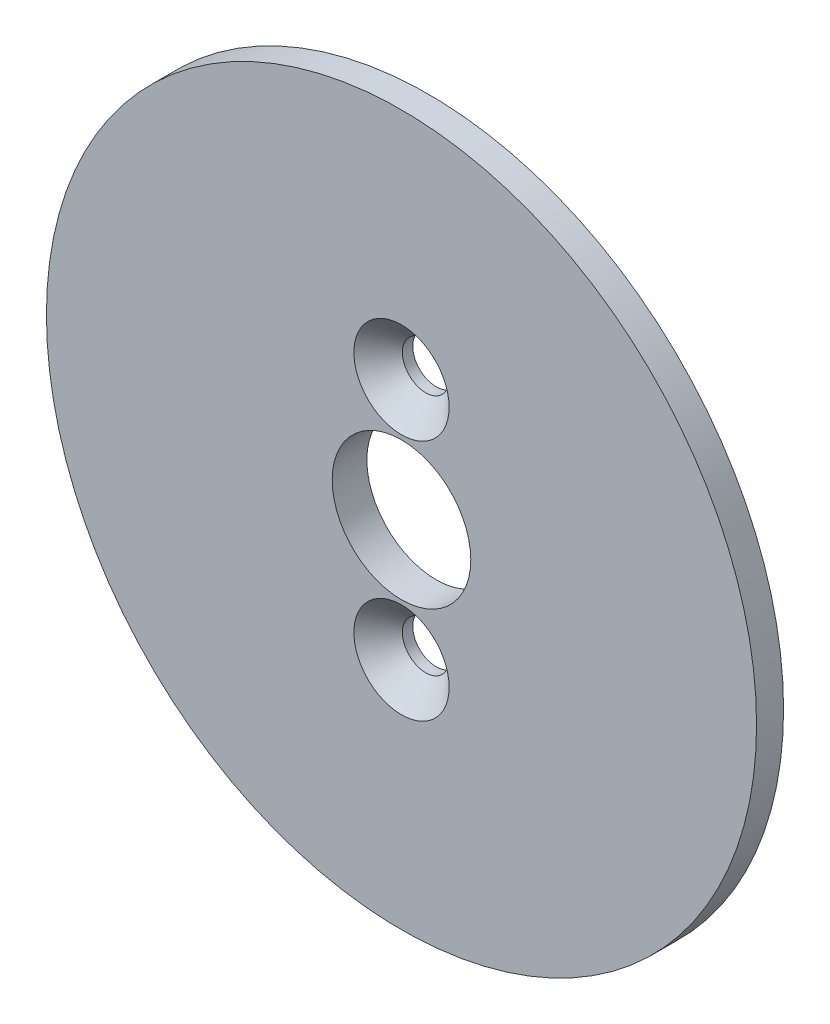
SolidWorks part; units mm, degrees
ref_plane "Front Plane" through (0, 0, 0) normal (0, 0, 1) x (1, 0, 0)
ref_plane "Top Plane" through (0, 0, 0) normal (0, 1, 0) x (1, 0, 0)
ref_plane "Right Plane" through (0, 0, 0) normal (1, 0, 0) x (0, 0, -1)
ref_axis "Axis1" through (0, 0, -0.1) along (0, 0, 1)
sketch "Sketch1" plane through (0, 0, 0) normal (0, 0, 1) x (1, 0, 0)
  circle A0 centre (0, 0) radius 20.5
extrude "Boss-Extrude1" add sketch "Sketch1" along normal blind 2
sketch "Sketch2" plane through (0, 0, 2) normal (-1, 0, 0) x (0, 0, 1)
  line L1 (-2, 18) -> (-1.5589, 20.5014)
  line L2 (-2, 18) -> (-2, 20.5014)
  line L3 (-2, 20.5014) -> (-1.5589, 20.5014)
  point P0 (-2, 20.4907)
revolve "Cut-Revolve1" cut sketch "Sketch2" angle 360 about axis through (0, 0, -0.1) along (0, 0, 1)
sketch "Sketch3" plane through (0, 0, 0) normal (0, 0, -1) x (-1, 0, 0)
  circle A0 centre (0, 0) radius 4
extrude "Cut-Extrude1" cut sketch "Sketch3" against normal up to next
sketch "Sketch4" plane through (0, 0, 2) normal (0, 0, 1) x (1, 0, 0)
  point P0 (0, 7)
  point P2 (0, -7)
  point P5 (0, 0)
  point P6 (0, 0)
hole_wizard "CSK for M3 Flat Countersunk Head Screw1" positions "Sketch4" profile "Sketch5" countersink size "M3" standard "JIS" end condition up to next
sketch "Sketch5" plane through (0, 7, 2) normal (1, 0, 0) x (0, -1, 0)
  line L0 (0, 0) -> (0, 2)
  line L1 (0, 2) -> (1.35, 2)
  line L2 (1.35, 2) -> (1.35, 1.4)
  line L3 (1.35, 1.4) -> (2.75, 0)
  line L5 (2.75, 0) -> (0, 0)
  line L6 (-1.35, 1.4) -> (-2.75, 0) construction
  line L11 (0, -6.35) -> (0, 107.95) construction
  dimension "Thru Hole Dia." = 2.7
  dimension "Thru Hole Depth" = 2
  dimension "Near C'Sink Dia." = 5.5
  dimension "Near C'Sink Angle" = 90
